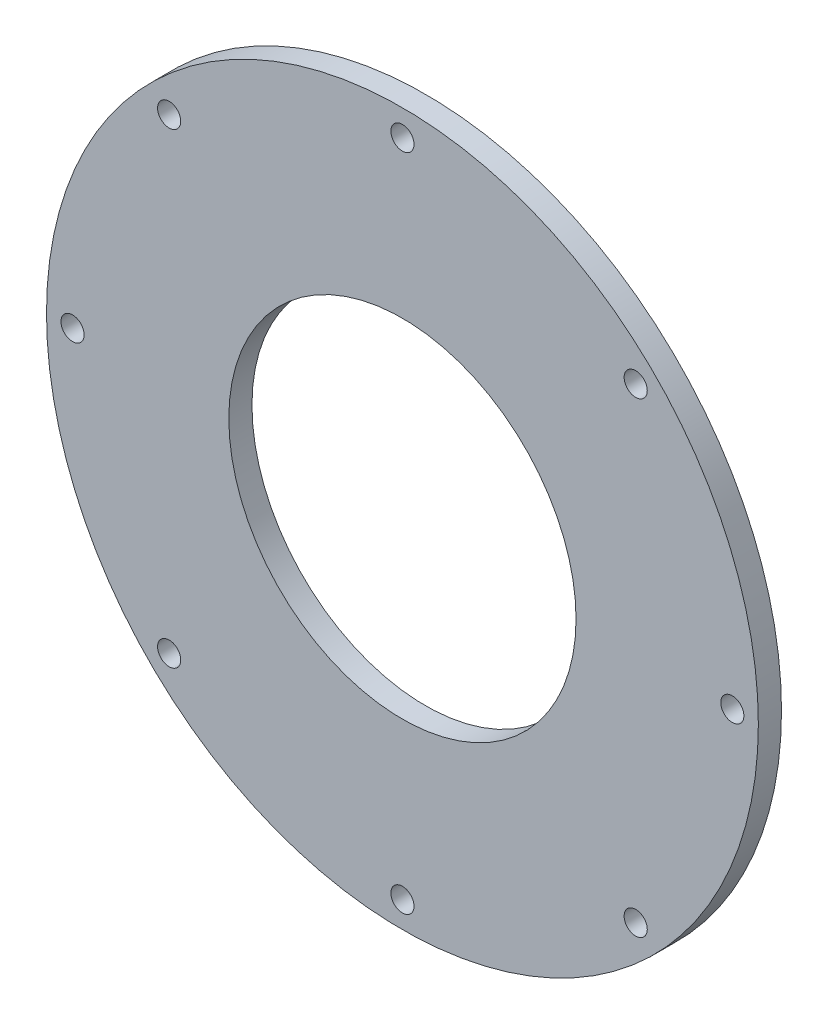
SolidWorks part; units mm, degrees
ref_plane "前视基准面" through (0, 0, 0) normal (0, 0, 1) x (1, 0, 0)
ref_plane "上视基准面" through (0, 0, 0) normal (0, 1, 0) x (1, 0, 0)
ref_plane "右视基准面" through (0, 0, 0) normal (1, 0, 0) x (0, 0, -1)
sketch "草图1" plane through (0, 0, 0) normal (0, 0, 1) x (1, 0, 0)
  line L0 (0, -52.5) -> (0, -61.5) construction
  line L1 (0, 0) -> (36.1973, 0) construction
  line L2 (0, 0) -> (39.2724, -22.6739) construction
  circle A1 centre (0, 0) radius 61.5
  circle A3 centre (0, 0) radius 52.5 construction
  circle A4 centre (0, -57) radius 2
  circle A5 centre (0, -57) radius 3.8 construction
  circle A6 centre (-40.3051, -40.3051) radius 2
  circle A7 centre (-57, 0) radius 2
  circle A8 centre (-40.3051, 40.3051) radius 2
  circle A9 centre (0, 0) radius 23.75 construction
  circle A10 centre (0, 0) radius 22.5 construction
  circle A11 centre (0, -23.75) radius 2.6
  circle A12 centre (-20.5681, 11.875) radius 2.6
  circle A13 centre (20.5681, 11.875) radius 2.6
  circle A14 centre (19.4856, -11.25) radius 2.6
  circle A15 centre (-19.4856, -11.25) radius 2.6
  circle A16 centre (0, 22.5) radius 2.6
  circle A17 centre (0, 0) radius 15.5
  circle A18 centre (0, 57) radius 2
  circle A19 centre (40.3051, 40.3051) radius 2
  circle A20 centre (57, 0) radius 2
  circle A21 centre (40.3051, -40.3051) radius 2
  dimension "D1" = 47.5
  dimension "D2" = 123
  dimension "D3" = 105
  dimension "D4" = 7.6
  dimension "D6" = 45
  dimension "D7" = 5.2
  dimension "D9" = 5.2
  dimension "D10" = 31
  dimension "D8" = 30
  dimension "D5" = 8
extrude "凸台-拉伸1" add sketch "草图1" along normal blind 4
sketch "草图2" plane through (0, 0, 4) normal (0, 0, 1) x (1, 0, 0)
  circle A0 centre (0, 0) radius 30
  dimension "D1" = 60
extrude "切除-拉伸1" cut sketch "草图2" against normal blind 10
